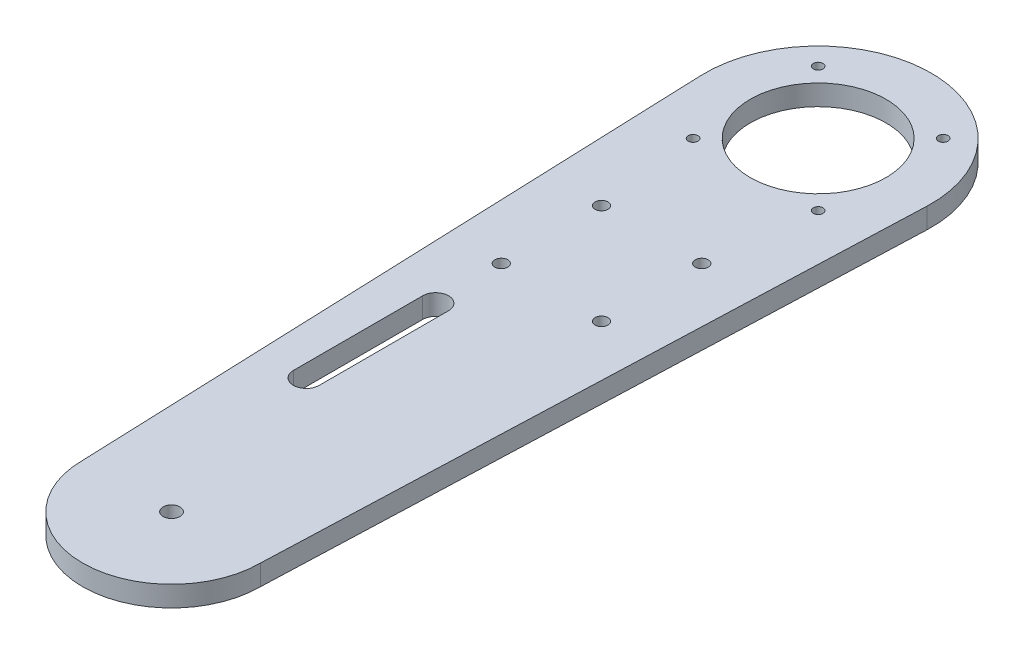
SolidWorks part; units mm, degrees
ref_plane "Front Plane" through (0, 0, 0) normal (0, 0, 1) x (1, 0, 0)
ref_plane "Top Plane" through (0, 0, 0) normal (0, 1, 0) x (1, 0, 0)
ref_plane "Right Plane" through (0, 0, 0) normal (1, 0, 0) x (0, 0, -1)
sketch "Sketch1" plane through (0, 0, 0) normal (0, 1, 0) x (1, 0, 0)
  line L0 (27.5, 0) -> (34.9753, 198.6841)
  line L1 (-27.5, 0) -> (-34.9753, 198.6841)
  arc A0 (-27.5, 0) -> (27.5, 0) centre (0, 0) ccw
  arc A3 (34.9753, 198.6841) -> (-34.9753, 198.6841) centre (0, 200) ccw
  dimension "D1" = 55
  dimension "D3" = 200
  dimension "D2" = 70
extrude "Boss-Extrude1" add sketch "Sketch1" along normal blind 6.35
sketch "Sketch2" plane through (0, 6.35, 0) normal (0, 1, 0) x (1, 0, 0)
  circle A0 centre (0, 0) radius 2.6
  dimension "D1" = 5.2
extrude "Cut-Extrude1" cut sketch "Sketch2" against normal through all
sketch "Esquisse4" plane through (0, 6.35, 0) normal (0, 1, 0) x (1, 0, 0)
  circle A0 centre (0, 200) radius 35
  arc A1 (34.9753, 198.6841) -> (-34.9753, 198.6841) centre (0, 200) ccw construction
sketch "Esquisse3" plane through (0, 6.35, 0) normal (0, 1, 0) x (1, 0, 0)
  circle A1 centre (0, 200) radius 21
  dimension "D1" = 42
extrude "Enlèv. mat.-Extru.2" cut sketch "Esquisse3" against normal through all
sketch "Esquisse5" plane through (0, 6.35, 0) normal (0, 1, 0) x (1, 0, 0)
  circle A0 centre (0, 200) radius 27.35
  dimension "D1" = 54.7
sketch "Esquisse7" plane through (0, 6.35, 0) normal (0, 1, 0) x (1, 0, 0)
  line L0 (-19.3394, 180.6606) -> (19.3394, 180.6606) construction
  line L1 (19.3394, 180.6606) -> (19.3394, 219.3394) construction
  line L2 (19.3394, 219.3394) -> (-19.3394, 219.3394) construction
  line L3 (-19.3394, 219.3394) -> (-19.3394, 180.6606) construction
  circle A0 centre (-19.3394, 219.3394) radius 1.5
  circle A1 centre (0, 200) radius 27.35 construction
  circle A2 centre (19.3394, 219.3394) radius 1.5
  circle A3 centre (19.3394, 180.6606) radius 1.5
  circle A4 centre (-19.3394, 180.6606) radius 1.5
  point P12 (0, 180.6606)
  dimension "D1" = 3
extrude "Enlèv. mat.-Extru.3" cut sketch "Esquisse7" against normal through all
sketch "Esquisse10" plane through (0, 0, 0) normal (1, 0, 0) x (0, 0, -1)
  line L0 (200, 30.779) -> (200, -18.079) construction
  point P4 (200, 6.35)
sketch "Esquisse8" plane through (0, 6.35, 0) normal (0, 1, 0) x (1, 0, 0)
  line L0 (18.4733, 182.1606) -> (20.2054, 182.1606)
  line L1 (20.2054, 182.1606) -> (21.0714, 180.6606)
  line L2 (21.0714, 180.6606) -> (20.2054, 179.1606)
  line L3 (20.2054, 179.1606) -> (18.4733, 179.1606)
  line L4 (18.4733, 179.1606) -> (17.6073, 180.6606)
  line L5 (17.6073, 180.6606) -> (18.4733, 182.1606)
  circle A1 centre (19.3394, 180.6606) radius 1.5 construction
extrude "Enlèv. mat.-Extru.5" [suppressed] cut sketch "Esquisse8" against normal through all
pattern_circular "Répétition circulaire1" [suppressed] count 4 over 360 about axis through (0, 30.779, -200) along (0, -1, 0)
sketch "Sketch4" plane through (0, 6.35, 0) normal (0, 1, 0) x (1, 0, 0)
  line L0 (-15, 56.7) -> (-15, 96.7) construction
  line L1 (-19, 56.7) -> (-19, 96.7)
  line L2 (-11, 56.7) -> (-11, 96.7)
  arc A0 (-19, 56.7) -> (-11, 56.7) centre (-15, 56.7) ccw
  arc A1 (-11, 96.7) -> (-19, 96.7) centre (-15, 96.7) ccw
  point P4 (-15, 76.7)
  dimension "D1" = 4
extrude "Cut-Extrude3" cut sketch "Sketch4" against normal through all
sketch "Sketch5" plane through (0, 0, 0) normal (0, -1, 0) x (1, 0, 0)
  circle A0 centre (15.5, -117.5) radius 2
  circle A1 centre (15.5, -148.5) radius 2
  circle A2 centre (-15.5, -148.5) radius 2
  circle A3 centre (-15.5, -117.5) radius 2
  dimension "D1" = 4
extrude "Cut-Extrude4" cut sketch "Sketch5" against normal through all
